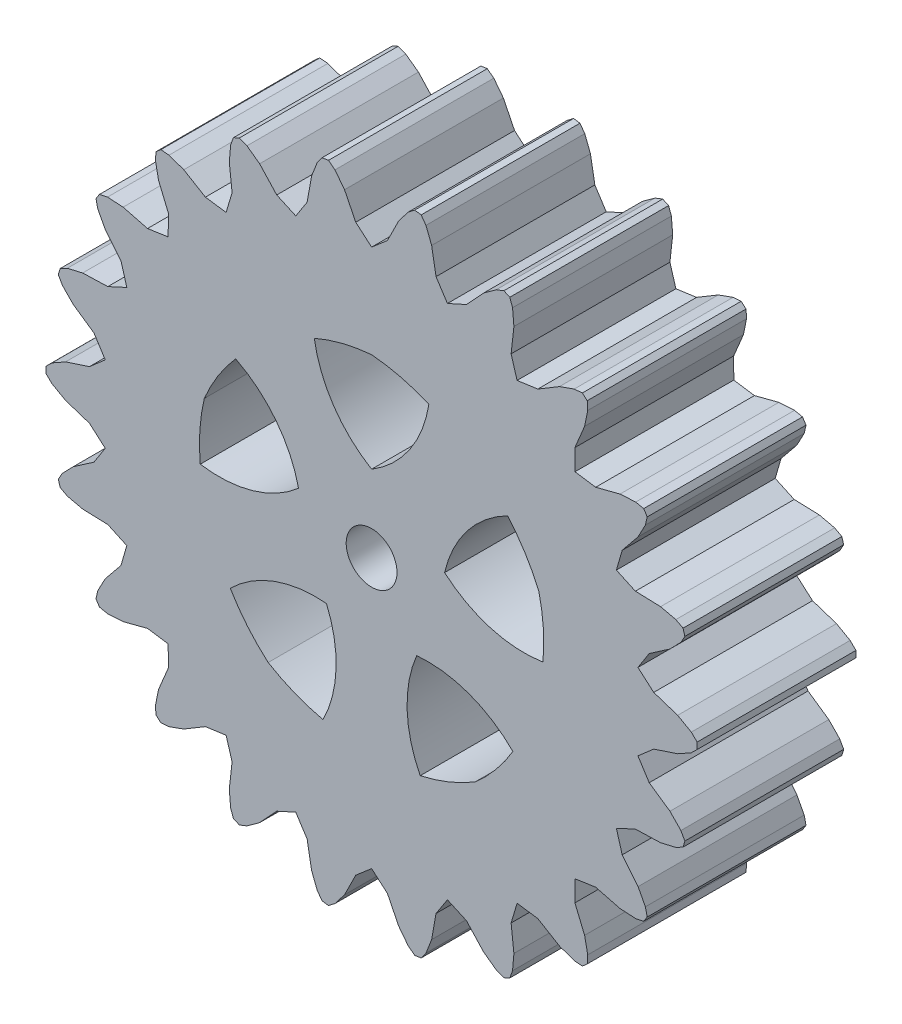
SolidWorks part; units mm, degrees
ref_plane "Front Plane" through (0, 0, 0) normal (0, 0, 1) x (1, 0, 0)
ref_plane "Top Plane" through (0, 0, 0) normal (0, 1, 0) x (1, 0, 0)
ref_plane "Right Plane" through (0, 0, 0) normal (1, 0, 0) x (0, 0, -1)
sketch "Sketch1" plane through (0, 0, 0) normal (0, 0, 1) x (1, 0, 0)
  line L1 (1.2374, -1.2374) -> (-1.2374, -1.2374) construction
  line L2 (1.2374, -1.2374) -> (1.2374, 1.2374) construction
  line L3 (1.2374, 1.2374) -> (-1.2374, 1.2374) construction
  line L4 (-1.2374, -1.2374) -> (-1.2374, 1.2374) construction
  line L5 (1.2374, -1.2374) -> (-1.2374, 1.2374) construction
  line L6 (1.2374, 1.2374) -> (-1.2374, -1.2374) construction
  circle A0 centre (0, 0) radius 20.5
  circle A1 centre (0, 0) radius 1.75 construction
  dimension "D1" = 41
  dimension "D2" = 3.5
extrude "Boss-Extrude1" add sketch "Sketch1" along normal blind 10
sketch "Sketch2" plane through (0, 0, 0) normal (0, 0, 1) x (1, 0, 0)
  line L0 (0, 0) -> (0, 10.088) construction
  line L1 (0, 16.9447) -> (-0.9985, 17.8041)
  line L8 (-2.7154, 20.3194) -> (0, 24.5037)
  line L11 (-0.9985, 17.8041) -> (-1.7043, 19.2252)
  line L12 (-1.7043, 19.2252) -> (-2.3066, 20.0063)
  line L13 (-2.3066, 20.0063) -> (-2.7154, 20.3194)
  line L14 (2.3066, 20.0063) -> (2.7154, 20.3194)
  line L15 (1.7043, 19.2252) -> (2.3066, 20.0063)
  line L16 (0.9985, 17.8041) -> (1.7043, 19.2252)
  line L17 (2.7154, 20.3194) -> (0, 24.5037)
  line L18 (0, 16.9447) -> (0.9985, 17.8041)
  circle A14 centre (0, 0) radius 20.5 construction
  point P16 (0, 20.5)
extrude "Cut-Extrude1" cut sketch "Sketch2" along normal through all
sketch "Sketch3" plane through (0, 0, 0) normal (0, 0, 1) x (1, 0, 0)
  circle A0 centre (0, 0) radius 7.5
  dimension "D1" = 15
sketch "Sketch4" plane through (0, 0, 10) normal (0, 0, 1) x (1, 0, 0)
  circle A0 centre (0, 0) radius 1.6
  dimension "D1" = 3.2
extrude "Cut-Extrude2" cut sketch "Sketch4" against normal through all both and the other way through all
pattern_circular "CirPattern1" count 22 over 360 about axis through (0, 0, 0) along (0, 0, 1) of "Cut-Extrude1"
sketch "Sketch5" plane through (0, 0, 0) normal (0, 0, 1) x (1, 0, 0)
  line L0 (0, 0) -> (0, 16.5734) construction
  arc A0 (0, 4.8339) -> (-3.6077, 10.172) centre (3.9153, 11.3681) cw
  arc A1 (-3.6077, 10.172) -> (0, 11.0786) centre (0.9488, -0.3284) cw
  arc A2 (3.6077, 10.172) -> (0, 11.0786) centre (-0.9488, -0.3284) ccw
  arc A3 (0, 4.8339) -> (3.6077, 10.172) centre (-3.9153, 11.3681) ccw
  point P7 (3.6077, 10.172)
extrude "Cut-Extrude4" cut sketch "Sketch5" along normal through all both and the other way through all
pattern_circular "CirPattern2" count 5 over 360 about axis through (0, 0, 0) along (0, 0, 1) of "Cut-Extrude4"
equation "\"circle\"=41"
equation "\"D1@Sketch1\"=\"circle\""
equation "\"separator_width\"=45"
equation "\"big-gear-thiccness\"=2"
equation "\"D1@Boss-Extrude1\"=10"
